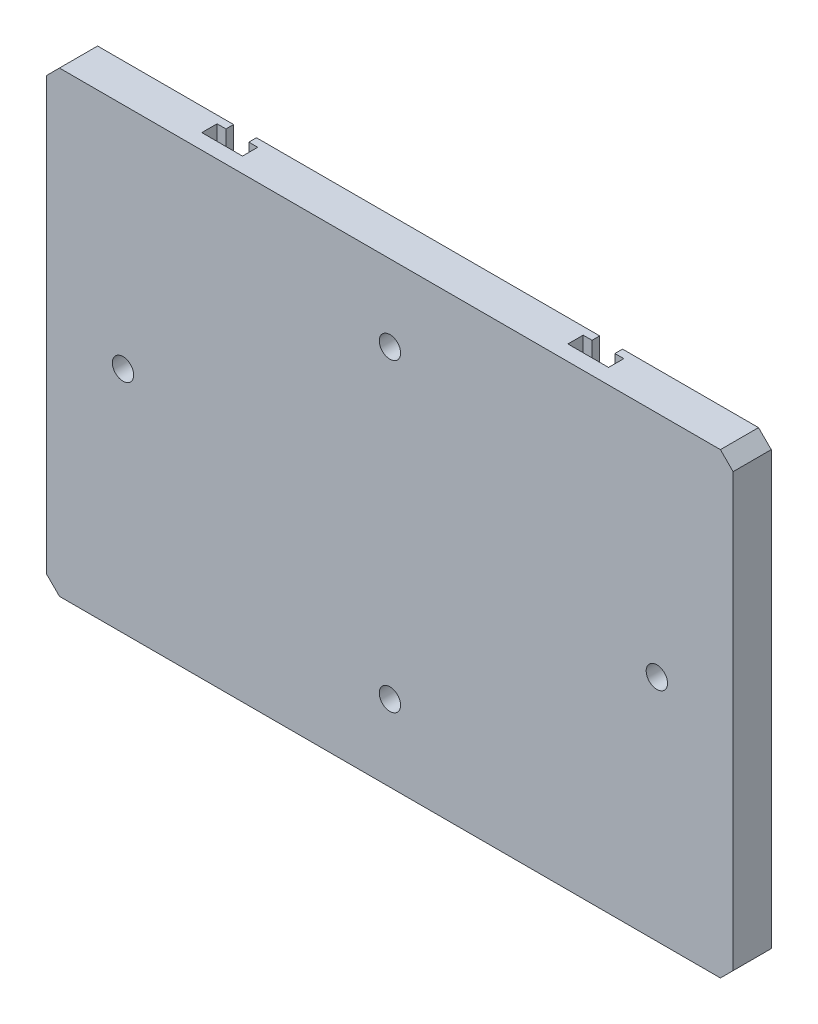
SolidWorks part; units mm, degrees
ref_plane "前视基准面" through (0, 0, 0) normal (0, 0, 1) x (1, 0, 0)
ref_plane "上视基准面" through (0, 0, 0) normal (0, 1, 0) x (1, 0, 0)
ref_plane "右视基准面" through (0, 0, 0) normal (1, 0, 0) x (0, 0, -1)
sketch "草图1" plane through (0, 0, 0) normal (0, 0, 1) x (1, 0, 0)
  line L1 (0, 0) -> (270, 0)
  line L2 (0, 0) -> (0, 180)
  line L3 (0, 180) -> (270, 180)
  line L4 (270, 0) -> (270, 180)
  dimension "D1" = 270
  dimension "D2" = 180
extrude "凸台-拉伸1" add sketch "草图1" along normal blind 15
chamfer "倒角1" distance 5 angle 45 4 edges at (0, 0, 7.5) (270, 0, 7.5) (270, 180, 7.5) (0, 180, 7.5)
hole_wizard "M8 凹头盖螺钉的柱形沉头孔1" positions "草图3" profile "草图2" counterbore size "M8" standard "Ansi Metric" end condition through all
sketch "草图3" plane through (0, 0, 0) normal (0, 0, -1) x (-1, 0, 0)
  point P0 (-240, 90)
  point P3 (-30, 90)
  point P6 (-135, 30)
  point P9 (-135, 150)
sketch "草图2" plane through (240, 90, 0) normal (1, 0, 0) x (0, 1, 0)
  line L0 (0, 0) -> (0, 15)
  line L1 (0, 15) -> (4.2, 15)
  line L3 (4.2, 15) -> (4.2, 8)
  line L4 (4.2, 8) -> (7.5, 8)
  line L5 (7.5, 8) -> (7.5, 0)
  line L7 (7.5, 0) -> (0, 0)
  line L11 (0, -6.35) -> (0, 107.95) construction
  dimension "通孔孔直径" = 8.4
  dimension "通孔孔深度" = 15
  dimension "柱形沉头孔直径" = 15
  dimension "柱形沉头孔深度" = 8
sketch "草图4" plane through (0, 180, 0) normal (0, 1, 0) x (1, 0, 0)
  line L0 (265, 0) -> (5, 0) construction
  line L1 (55, -9) -> (71, -9)
  line L2 (55, -9) -> (55, -3)
  line L3 (55, -3) -> (58.5, -3)
  line L4 (71, -9) -> (71, -3)
  line L5 (0, -15) -> (0, 0) construction
  line L6 (58.5, -3) -> (58.5, 0)
  line L7 (58.5, 0) -> (67.5, 0)
  line L8 (67.5, -3) -> (67.5, 0)
  line L9 (67.5, -3) -> (71, -3)
  line L10 (135, -22.7913) -> (135, 8.4449) construction
  line L11 (202.5, -3) -> (199, -3)
  line L12 (202.5, -3) -> (202.5, 0)
  line L13 (211.5, 0) -> (202.5, 0)
  line L14 (211.5, -3) -> (211.5, 0)
  line L15 (199, -9) -> (199, -3)
  line L16 (215, -3) -> (211.5, -3)
  line L17 (215, -9) -> (215, -3)
  line L18 (215, -9) -> (199, -9)
  dimension "D1" = 16
  dimension "D2" = 9
  dimension "D3" = 3.5
  dimension "D4" = 6
  dimension "D5" = 3
  dimension "D6" = 55
extrude "切除-拉伸1" cut sketch "草图4" against normal through all
